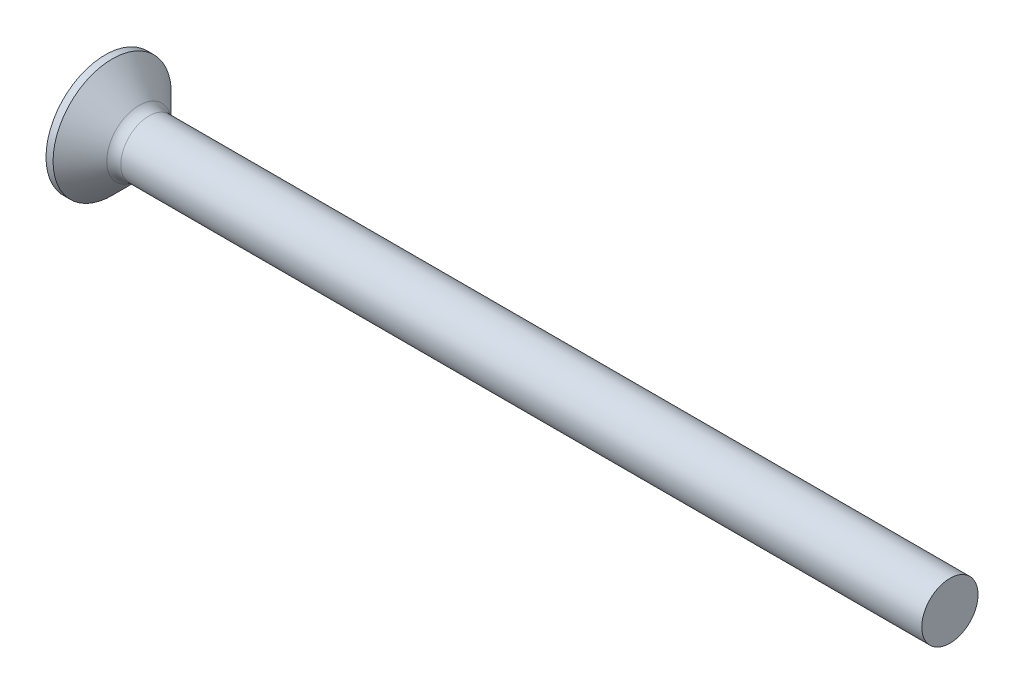
SolidWorks part; units mm, degrees
ref_plane "Plane1" through (0, 0, 0) normal (0, 0, 1) x (1, 0, 0)
ref_plane "Plane2" through (0, 0, 0) normal (0, 1, 0) x (1, 0, 0)
ref_plane "Plane3" through (0, 0, 0) normal (1, 0, 0) x (0, 0, -1)
other "Configuration Table"
sketch "BodySke" plane through (0, 0, 0) normal (0, 0, 1) x (1, 0, 0)
  line L0 (0, 0) -> (61, 0)
  line L1 (61, 0) -> (61, 2)
  line L2 (61, 2) -> (3.7, 2)
  line L3 (1.5, -4.2) -> (3.7, -2) construction
  line L4 (-15.875, 0) -> (82.55, 0) construction
  line L5 (1.5, 4.2) -> (3.7, 2)
  line L6 (4.4, 5.175) -> (4.4, -10.7) construction
  line L7 (21, 2.7793) -> (21, -13.0957) construction
  line L8 (1.5, 4.2) -> (1, 4.2)
  arc A0 (0, 0) -> (1, 4.2) centre (9.32, 0) cw
  dimension "Head_ang" = 90
  dimension "Diameter" = 4
  dimension "Advance" = 0.7
  dimension "Thread_nom" = 40
  dimension "Oval_ht" = 1
  dimension "Side_ht" = 2.7
  dimension "Head_dia" = 8.4
  dimension "Length" = 60
revolve "Base-Revolve" add sketch "BodySke" angle 360 about L4
cosmetic thread "ThreadCosmetic" [suppressed] parameters "Thread_length"=40, "Thread_minor"=3.22
fillet "Fillet1" radius 1 1 edges at (3.7, 0, 2)
sketch "Sketch3" plane through (0, 0, 0) normal (1, 0, 0) x (0, 0, -1)
  line L0 (0.515, -2.5) -> (-0.515, -2.5)
  line L1 (0.515, -2.5) -> (0.515, 2.5)
  line L2 (-0.515, 2.5) -> (0.515, 2.5)
  line L3 (-0.515, 2.5) -> (-0.515, -2.5)
  dimension "Cross_width" = 1.03
  dimension "D1" = 0.515
  dimension "Cross_dia" = 5
  dimension "D2" = 2.5
ref_plane "Plane4" through (3.1, 0, 0) normal (1, 0, 0) x (0, 0, -1)
sketch "Sketch4" plane through (3.1, 0, 0) normal (1, 0, 0) x (0, 0, -1)
  line L0 (0.515, -0.9544) -> (-0.515, -0.9544)
  line L1 (0.515, -0.9544) -> (0.515, 0.9544)
  line L2 (-0.515, 0.9544) -> (0.515, 0.9544)
  line L3 (-0.515, 0.9544) -> (-0.515, -0.9544)
  dimension "D1" = 1.03
  dimension "D2" = 1.9088
  dimension "D3" = 0.515
  dimension "D4" = 0.9544
loft "Recess" cut profiles "Sketch3", "Sketch4"
pattern_circular "RecPat" count 2 every 90 about axis through (0, 0, 0) along (1, 0, 0) of "Recess"
sketch "RecCorSke" plane through (0, 0, 0) normal (0, 0, 1) x (1, 0, 0)
  line L0 (-3.175, 0) -> (15.875, 0) construction
  line L2 (0, 0) -> (0, 1.0678)
  line L3 (0, 1.0678) -> (3.1, 0.851)
  line L4 (3.1, 0.851) -> (3.3765, 0)
  line L5 (3.3765, 0) -> (0, 0)
  dimension "Diameter" = 1.702
  dimension "Depth" = 3.1
  dimension "Draft_angle" = 4
  dimension "Bottom_angle" = 18
revolve "RecessCore" cut sketch "RecCorSke" angle 360 about L0
sketch "ThdSchSke" plane through (0, 0, 0) normal (0, 0, 1) x (1, 0, 0)
  line L0 (21, -1.61) -> (20.7269, -2)
  line L1 (21, -1.61) -> (21.2731, -2)
  line L2 (21.2731, -2) -> (21.2731, -2.5)
  line L3 (-3.175, 0) -> (5.1513, 0) construction
  line L5 (21.2731, -2.5) -> (20.7269, -2.5)
  line L6 (20.7269, -2.5) -> (20.7269, -2)
  dimension "Diameter" = 4
  dimension "SideAngle" = 55
  dimension "VeeAngle" = 70
  dimension "Thread_minor" = 3.22
  dimension "Overcut" = 5
  dimension "Start" = 21
revolve "ThreadSchematic" [suppressed] cut sketch "ThdSchSke" angle 360 about L3
pattern_linear "ThdSchPat" [suppressed]
equation "\"D1@Sketch3\" = \"Cross_width@Sketch3\" / 2"
equation "\"D2@Sketch3\" = \"Cross_dia@Sketch3\" / 2"
equation "\"Depth@RecCorSke\" = \"Cross_depth@Plane4\""
equation "\"D1@Sketch4\" = \"Cross_width@Sketch3\""
equation "\"D2@Sketch4\" = \"Cross_dia@Sketch3\" - 2.0 * \"Cross_depth@Plane4\" * tan(26.5  * 0.017453292)"
equation "\"D3@Sketch4\" = \"D1@Sketch4\" / 2"
equation "\"D4@Sketch4\" = \"D2@Sketch4\" / 2"
equation "\"Thread_length@ThreadCosmetic\" = ((sgn( (\"Length@BodySke\" - \"Advance@BodySke\" - \"Side_ht@BodySke\" ) - \"Thread_nom@BodySke\" )-1)*( (\"Length@BodySke\" - \"Advance@BodySke\" - \"Side_ht@BodySke\" ) - \"Thread_nom@BodySke\" ))/-2+ \"Thread_nom@BodySke\""
equation "\"Thread_minor@ThdSchSke\" = \"Thread_minor@ThreadCosmetic\""
equation "\"Diameter@ThdSchSke\" = \"Diameter@BodySke\""
equation "\"Overcut@ThdSchSke\" = \"Diameter@BodySke\" * 1.25"
equation "\"Start@ThdSchSke\" = \"Oval_ht@BodySke\" + \"Length@BodySke\" - \"Thread_length@ThreadCosmetic\"  '---Countersunk---"
equation "\"Num_threads@ThdSchPat\" = int( \"Thread_length@ThreadCosmetic\" / \"Advance@BodySke\" + 0.999 )  + 1"
equation "\"Advance@ThdSchPat\" = \"Thread_length@ThreadCosmetic\" /  (\"Num_threads@ThdSchPat\" - 1) 'relax it"
